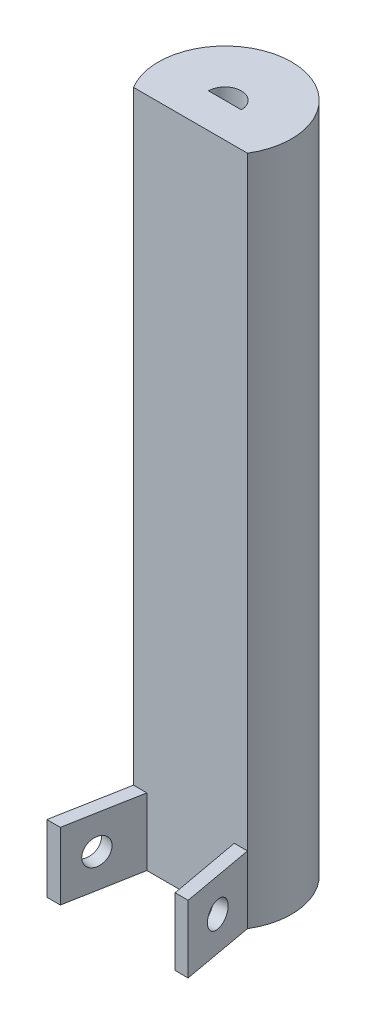
SolidWorks part; units mm, degrees
ref_plane "Front Plane" through (0, 0, 0) normal (0, 0, 1) x (1, 0, 0)
ref_plane "Top Plane" through (0, 0, 0) normal (0, 1, 0) x (1, 0, 0)
ref_plane "Right Plane" through (0, 0, 0) normal (1, 0, 0) x (0, 0, -1)
sketch "Sketch1" plane through (0, 0, 0) normal (0, 1, 0) x (1, 0, 0)
  circle A1 centre (0, 0) radius 12.6252
extrude "Boss-Extrude1" add sketch "Sketch1" against normal blind 127.254 contours A1
sketch "Sketch2" plane through (0, -127.254, 0) normal (0, -1, 0) x (-1, 0, 0)
  line L0 (-10.8004, -6.538) -> (10.8004, -6.538)
  line L1 (10.8004, -6.538) -> (10.8004, -12.6252)
  line L2 (10.8004, -12.6252) -> (-10.8004, -12.6252)
  line L3 (-10.8004, -12.6252) -> (-10.8004, -6.538)
  circle A0 centre (0, 0) radius 12.6252 construction
extrude "Cut-Extrude1" cut sketch "Sketch2" against normal blind 155.702
sketch "Sketch3" plane through (0, -127.254, 0) normal (0, -1, 0) x (-1, 0, 0)
  line L0 (3.1262, 0) -> (-3.0916, 0)
  arc A1 (-3.0916, 0) -> (3.1262, 0) centre (0.0173, 0) cw
extrude "Cut-Extrude2" cut sketch "Sketch3" against normal blind 141.0817
sketch "Sketch4" plane through (0, -127.254, 0) normal (0, -1, 0) x (1, 0, 0)
  line L0 (-10.8004, 6.538) -> (-8.2748, 6.538)
  line L1 (-10.8004, 6.538) -> (10.8004, 6.538) construction
  line L2 (-8.2748, 6.538) -> (-10.8004, 20.3961)
  line L3 (-10.8004, 20.3961) -> (-13.3646, 20.3961)
  line L4 (-13.3646, 20.3961) -> (-10.8004, 6.538)
  line L5 (10.8004, 6.538) -> (8.2919, 6.538)
  line L6 (8.2919, 6.538) -> (10.8004, 20.3961)
  line L7 (10.8004, 20.3961) -> (13.2794, 20.3961)
  line L8 (13.2794, 20.3961) -> (10.8004, 6.538)
extrude "Boss-Extrude2" add sketch "Sketch4" against normal blind 12.7552 contours L4 L0 L2 L3
sketch "Sketch5" plane through (0, -127.254, 0) normal (0, -1, 0) x (1, 0, 0)
  line L0 (10.8004, 6.538) -> (8.2879, 6.538)
  line L1 (-8.2748, 6.538) -> (10.8004, 6.538) construction
  line L2 (8.2879, 6.538) -> (10.8004, 20.2585)
  line L3 (10.8004, 20.2585) -> (13.2656, 20.2585)
  line L4 (13.2656, 20.2585) -> (10.8004, 6.538)
extrude "Boss-Extrude3" add sketch "Sketch5" against normal blind 12.7552
sketch "Sketch6" plane through (9.3248, 0, -1.6754) normal (0.9842, 0, -0.1768) x (-0.1768, 0, -0.9842)
  circle A0 centre (-15.3149, -120.8323) radius 2.435
extrude "Cut-Extrude3" cut sketch "Sketch6" against normal blind 11.2312 contours A0
sketch "Sketch7" plane through (-9.2732, 0, -1.7159) normal (-0.9833, 0, -0.1819) x (-0.1819, 0, 0.9833)
  circle A0 centre (16.0693, -120.8764) radius 2.4723
extrude "Cut-Extrude4" cut sketch "Sketch7" against normal blind 10.9772 contours A0
